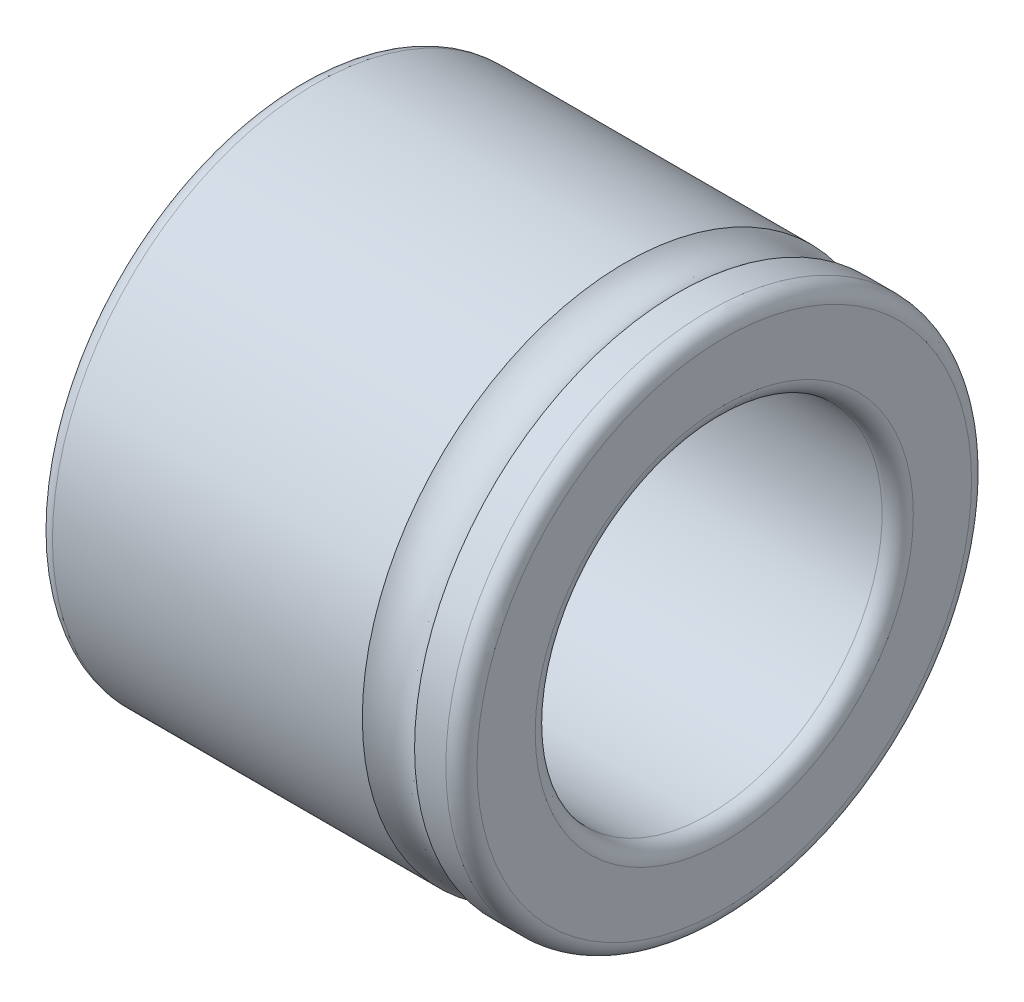
SolidWorks part; units mm, degrees
ref_plane "Front Plane" through (0, 0, 0) normal (0, 0, 1) x (1, 0, 0)
ref_plane "Top Plane" through (0, 0, 0) normal (0, 1, 0) x (1, 0, 0)
ref_plane "Right Plane" through (0, 0, 0) normal (1, 0, 0) x (0, 0, -1)
sketch "Sketch1" plane through (0, 0, 0) normal (0, 0, 1) x (1, 0, 0)
  line L0 (-18.5268, 11.1125) -> (6.6732, 11.1125)
  line L1 (7.6732, 12.1125) -> (7.6732, 15.8425)
  line L2 (6.6732, 16.8425) -> (4.6732, 16.8425)
  line L3 (-19.5268, 12.1125) -> (-19.5268, 15.8425)
  line L4 (-18.5268, 16.8425) -> (1.3268, 16.8425)
  line L5 (-23.3161, 0) -> (19.6206, 0) construction
  arc A0 (1.3268, 16.8425) -> (4.6732, 16.8425) centre (3, 18.7) ccw
  arc A1 (-19.5268, 12.1125) -> (-18.5268, 11.1125) centre (-18.5268, 12.1125) ccw
  arc A2 (6.6732, 11.1125) -> (7.6732, 12.1125) centre (6.6732, 12.1125) ccw
  arc A3 (7.6732, 15.8425) -> (6.6732, 16.8425) centre (6.6732, 15.8425) ccw
  arc A4 (-18.5268, 16.8425) -> (-19.5268, 15.8425) centre (-18.5268, 15.8425) ccw
  point P7 (-7.3268, 16.8425)
  point P13 (-19.5268, 11.1125)
  point P16 (7.6732, 11.1125)
  point P19 (7.6732, 16.8425)
  point P22 (-19.5268, 16.8425)
  dimension "D5" = 2.5
  dimension "D6" = 1
  dimension "D8" = 18.7
  dimension "D1" = 27.2
  dimension "D2" = 5.73
  dimension "D3" = 15
  dimension "D4" = 11.1125
  dimension "D7" = 2
  dimension "D9" = 3
revolve "Revolve1" add sketch "Sketch1" angle 360 about L5
